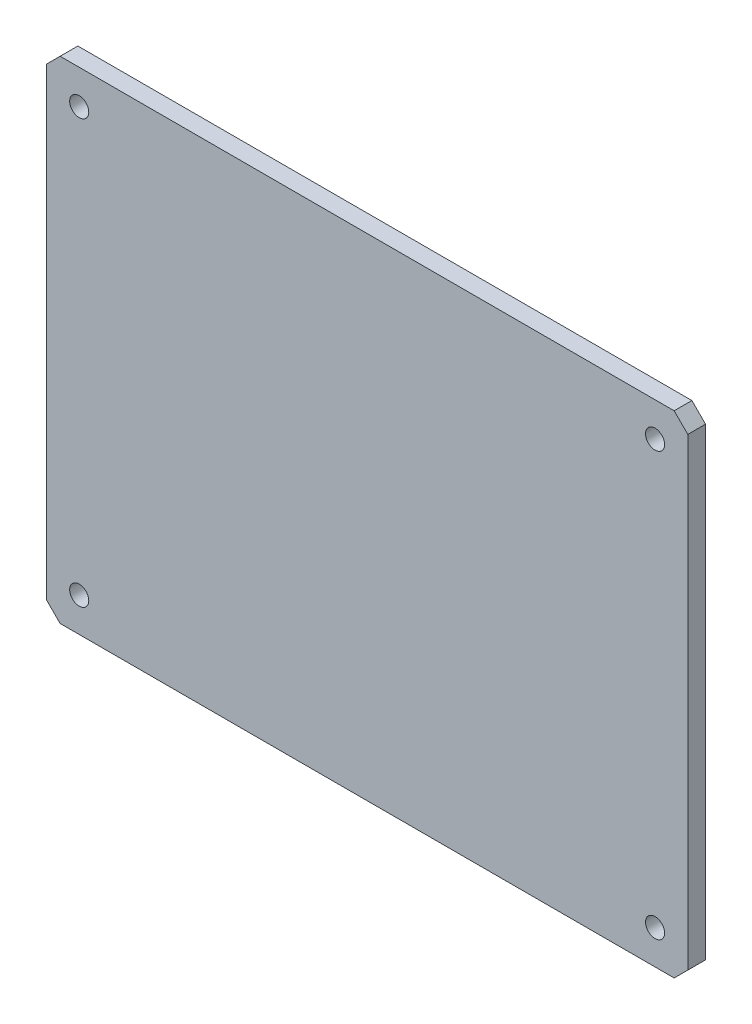
SolidWorks part; units mm, degrees
ref_plane "前视基准面" through (0, 0, 0) normal (0, 0, 1) x (1, 0, 0)
ref_plane "上视基准面" through (0, 0, 0) normal (0, 1, 0) x (1, 0, 0)
ref_plane "右视基准面" through (0, 0, 0) normal (1, 0, 0) x (0, 0, -1)
other "Configuration Table"
sketch "平盖和四个 Ø2.8 通孔 profile" plane through (0, 0, 0) normal (0, 0, 1) x (1, 0, 0)
  line L0 (-45, -36) -> (45, -36)
  line L1 (45, -36) -> (47, -34)
  line L2 (47, -34) -> (47, 34)
  line L3 (47, 34) -> (45, 36)
  line L4 (45, 36) -> (-45, 36)
  line L5 (-45, 36) -> (-47, 34)
  line L6 (-47, 34) -> (-47, -34)
  line L7 (-47, -34) -> (-45, -36)
  circle A0 centre (-42.2, -31) radius 1.4
  circle A1 centre (42.2, -31) radius 1.4
  circle A2 centre (-42.2, 31) radius 1.4
  circle A3 centre (42.2, 31) radius 1.4
extrude "平盖和四个 Ø2.8 通孔" add sketch "平盖和四个 Ø2.8 通孔 profile" along normal blind 2.6
